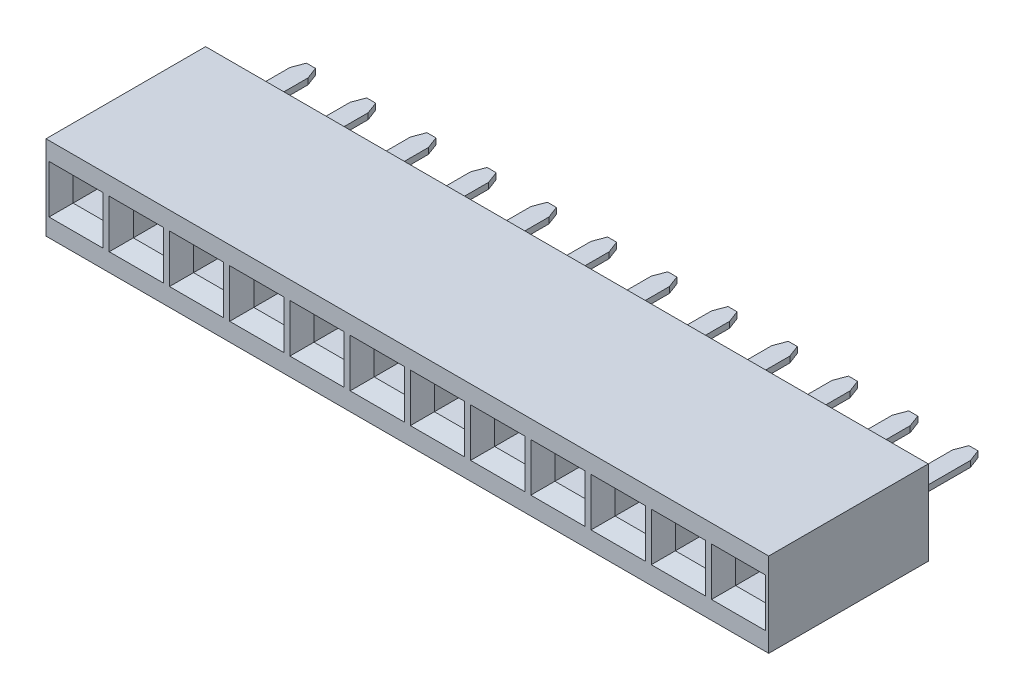
SolidWorks part; units mm, degrees
ref_plane "Front" through (0, 0, 0) normal (0, 0, 1) x (1, 0, 0)
ref_plane "Top" through (0, 0, 0) normal (0, 1, 0) x (1, 0, 0)
ref_plane "Right" through (0, 0, 0) normal (1, 0, 0) x (0, 0, -1)
sketch "Sketch1" plane through (0, 0, 0) normal (0, 0, 1) x (1, 0, 0)
  line L1 (1.27, -1.778) -> (-1.27, -1.778)
  line L2 (1.27, -1.778) -> (1.27, 1.778)
  line L3 (1.27, 1.778) -> (-1.27, 1.778)
  line L4 (-1.27, -1.778) -> (-1.27, 1.778)
  line L5 (1.27, -1.778) -> (-1.27, 1.778) construction
  line L6 (1.27, 1.778) -> (-1.27, -1.778) construction
  point P0 (0, 0)
  dimension "D1" = 3.556
  dimension "D2" = 2.54
extrude "Boss-Extrude1" add sketch "Sketch1" along normal blind 6.731
sketch "Sketch2" plane through (0, 0, 6.731) normal (0, 0, 1) x (1, 0, 0)
  line L1 (0.635, -0.508) -> (-0.635, -0.508)
  line L2 (0.635, -0.508) -> (0.635, 0.508)
  line L3 (0.635, 0.508) -> (-0.635, 0.508)
  line L4 (-0.635, -0.508) -> (-0.635, 0.508)
  line L5 (0.635, -0.508) -> (-0.635, 0.508) construction
  line L6 (0.635, 0.508) -> (-0.635, -0.508) construction
  point P0 (0, 0)
  dimension "D1" = 1.27
  dimension "D2" = 1.016
extrude "Cut-Extrude1" cut sketch "Sketch2" against normal offset from surface (5.461 mm away) 1.27 up to face at (0, 0, 0)
chamfer "Chamfer1" distance 0.508 angle 45 4 edges at (0.635, 0, 6.731) (0, -0.508, 6.731) (-0.635, 0, 6.731) (0, 0.508, 6.731)
sketch "Sketch3" plane through (0, 1.778, 0) normal (0, 1, 0) x (1, 0, 0)
  line L0 (-0.381, 0) -> (-0.381, 2.667)
  line L1 (1.27, 0) -> (-1.27, 0) construction
  line L2 (-0.381, 2.667) -> (-0.1905, 3.175)
  line L3 (-0.1905, 3.175) -> (0.1905, 3.175)
  line L4 (0.1905, 3.175) -> (0.381, 2.667)
  line L5 (0.381, 2.667) -> (0.381, 0)
  line L6 (0.381, 0) -> (-0.381, 0)
  line L7 (0, 3.175) -> (0, 0) construction
  dimension "D1" = 3.175
  dimension "D2" = 0.762
  dimension "D3" = 0.508
  dimension "D4" = 0.381
extrude "Boss-Extrude2" add sketch "Sketch3" along normal mid plane 0.254 from offset 1.778 offset against normal yes
pattern_linear "LPattern1" count 12 spacing 2.54 along (1, 0, 0) of "Boss-Extrude1", "Cut-Extrude1", "Chamfer1", "Boss-Extrude2"
